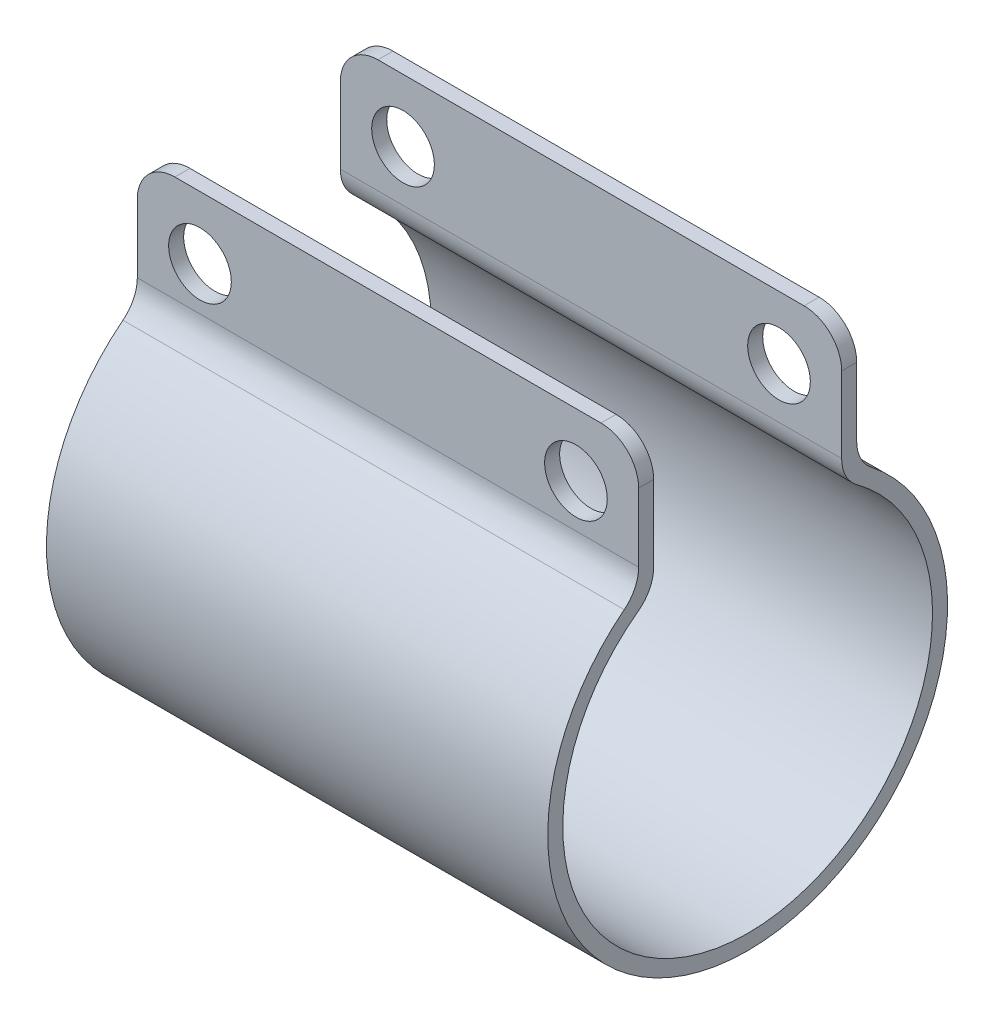
SolidWorks part; units mm, degrees
ref_plane "Front Plane" through (0, 0, 0) normal (0, 0, 1) x (1, 0, 0)
ref_plane "Top Plane" through (0, 0, 0) normal (0, 1, 0) x (1, 0, 0)
ref_plane "Right Plane" through (0, 0, 0) normal (1, 0, 0) x (0, 0, -1)
sketch "Sketch1" plane through (0, 0, 0) normal (1, 0, 0) x (0, 0, -1)
  line L0 (9.525, 16.1301) -> (9.525, 29.6778)
  line L1 (9.525, 29.6778) -> (11.049, 29.6778)
  line L2 (11.049, 29.6778) -> (11.049, 16.9778)
  line L3 (-9.525, 16.1301) -> (-9.525, 29.6778)
  line L4 (-9.525, 29.6778) -> (-11.049, 29.6778)
  line L5 (-11.049, 29.6778) -> (-11.049, 16.9778)
  circle A0 centre (0, 0) radius 17.4625 construction
  arc A1 (-9.525, 16.1301) -> (9.525, 16.1301) centre (0, 0) ccw
  arc A2 (-11.049, 16.9778) -> (11.049, 16.9778) centre (0, 0) ccw
  dimension "D1" = 34.925
  dimension "D2" = 1.27
  dimension "D3" = 1.524
  dimension "D4" = 1.524
  dimension "D5" = 19.05
  dimension "D6" = 12.7
extrude "Boss-Extrude1" add sketch "Sketch1" along normal blind 50.8
sketch "Sketch2" plane through (0, 0, 0) normal (0, 0, 1) x (1, 0, 0)
  line L0 (6.35, 23.3278) -> (44.45, 23.3278) construction
  line L1 (50.8, 29.6778) -> (0, 29.6778) construction
  line L2 (50.8, 29.6778) -> (50.8, 16.9778) construction
  circle A0 centre (6.35, 23.3278) radius 3.175
  circle A1 centre (44.45, 23.3278) radius 3.175
  point P6 (25.4, 29.6778)
  point P7 (25.4, 23.3278)
  point P10 (50.8, 23.3278)
  dimension "D1" = 6.35
  dimension "D2" = 38.1
extrude "Cut-Extrude1" cut sketch "Sketch2" against normal through all and the other way through all
fillet "Fillet1" radius 3.81 8 edges at (25.4, 16.9778, 11.049) (25.4, 16.9778, -11.049) (50.8, 29.6778, 10.287) (50.8, 29.6778, -10.287) (0, 29.6778, -10.287) (0, 29.6778, 10.287) (25.4, 16.1301, 9.525) (25.4, 16.1301, -9.525)
